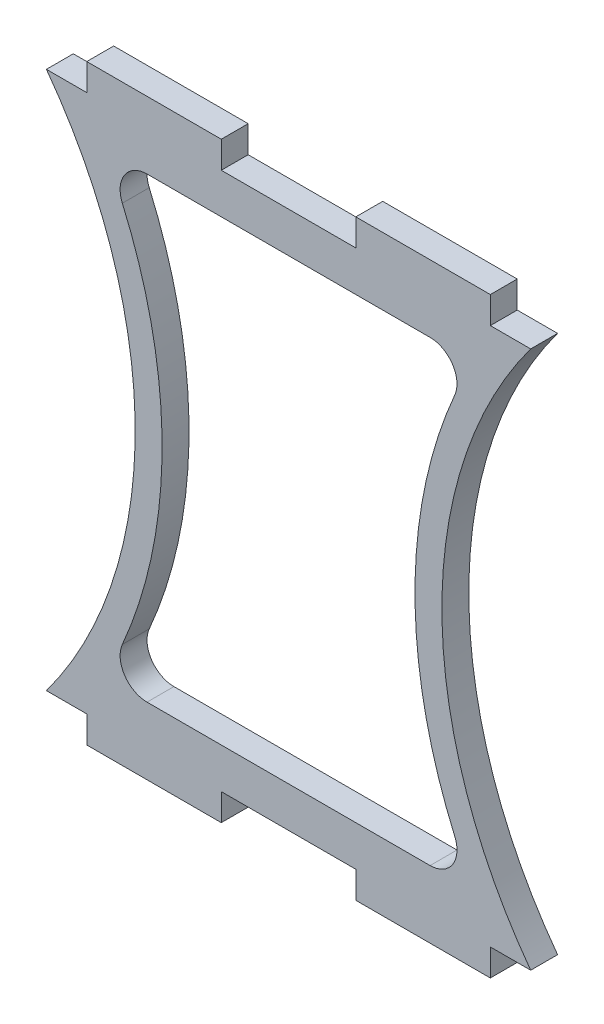
SolidWorks part; units mm, degrees
ref_plane "Front Plane" through (0, 0, 0) normal (0, 0, 1) x (1, 0, 0)
ref_plane "Top Plane" through (0, 0, 0) normal (0, 1, 0) x (1, 0, 0)
ref_plane "Right Plane" through (0, 0, 0) normal (1, 0, 0) x (0, 0, -1)
sketch "Sketch1" plane through (0, 0, 0) normal (0, 0, 1) x (1, 0, 0)
  line L0 (0, 30) -> (0, 0) construction
  line L1 (-18, 20) -> (-15, 20)
  line L2 (-5, 20) -> (-5, 22)
  line L3 (-18, -20) -> (-15, -20)
  line L4 (-5, 22) -> (-15, 22)
  line L5 (0, 0) -> (98.5, 0) construction
  line L6 (-10.521, -17) -> (10.521, -17)
  line L7 (-15, 22) -> (-15, 20)
  line L8 (-10.521, 17) -> (10.521, 17)
  line L9 (5, 20) -> (5, 22)
  line L10 (5, 22) -> (15, 22)
  line L11 (15, 22) -> (15, 20)
  line L12 (15, -22) -> (15, -20)
  line L13 (5, -22) -> (15, -22)
  line L14 (5, -20) -> (5, -22)
  line L15 (-5, -20) -> (-5, -22)
  line L16 (-5, -22) -> (-15, -22)
  line L17 (-15, -22) -> (-15, -20)
  line L18 (-5, -20) -> (5, -20)
  line L19 (15, -20) -> (18, -20)
  line L20 (15, 20) -> (18, 20)
  line L21 (-5, 20) -> (5, 20)
  arc A0 (18, 20) -> (18, -20) centre (45, 0) ccw
  arc A1 (-10.521, -17) -> (-12.3549, -14.2021) centre (-10.521, -15) cw
  arc A2 (-18, 20) -> (-18, -20) centre (-45, 0) cw
  arc A3 (12.3549, -14.2021) -> (10.521, -17) centre (10.521, -15) cw
  arc A4 (12.3549, 14.2021) -> (12.3549, -14.2021) centre (45, 0) ccw
  arc A5 (12.3549, 14.2021) -> (10.521, 17) centre (10.521, 15) ccw
  arc A6 (-12.3549, 14.2021) -> (-12.3549, -14.2021) centre (-45, 0) cw
  arc A7 (-12.3549, 14.2021) -> (-10.521, 17) centre (-10.521, 15) cw
  point P10 (16.3929, 21.1905)
  point P11 (16.3929, -21.1905)
  dimension "D1" = 2
  dimension "D4" = 20
extrude "Boss-Extrude1" add sketch "Sketch1" along normal blind 2
